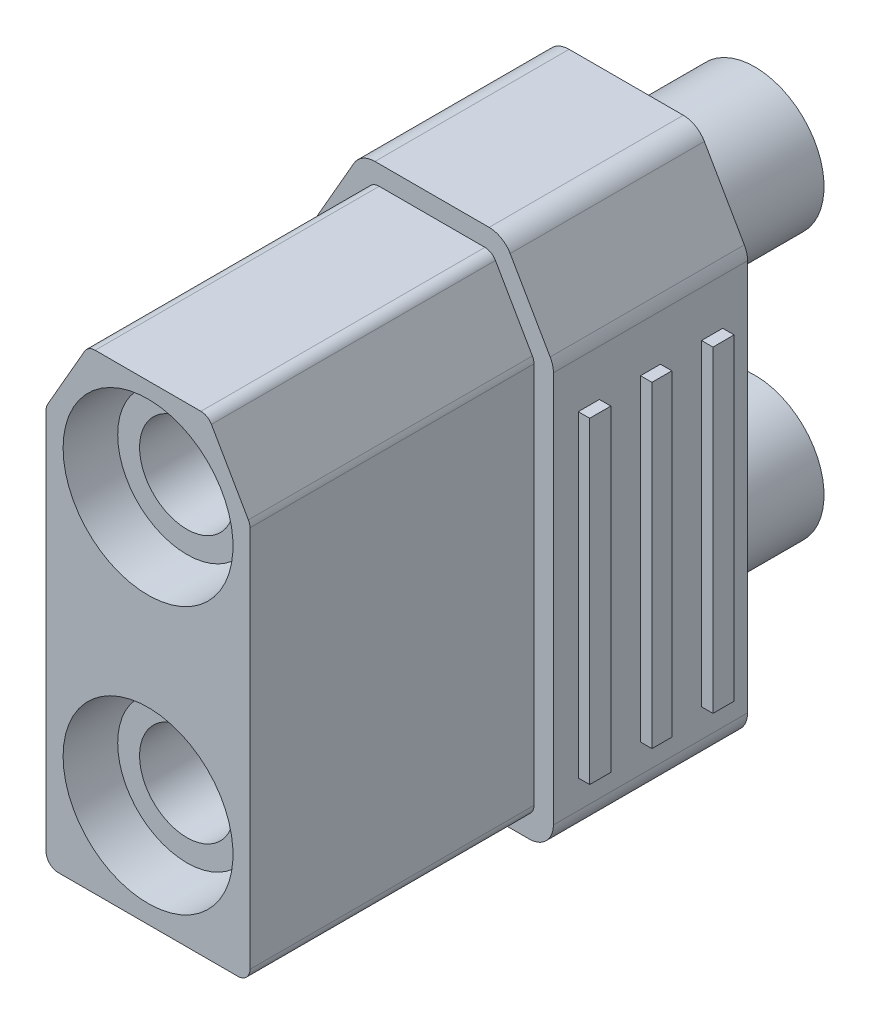
SolidWorks part; units mm, degrees
ref_plane "Front Plane" through (0, 0, 0) normal (0, 0, 1) x (1, 0, 0)
ref_plane "Top Plane" through (0, 0, 0) normal (0, 1, 0) x (1, 0, 0)
ref_plane "Right Plane" through (0, 0, 0) normal (1, 0, 0) x (0, 0, -1)
sketch "Sketch1" plane through (0, 0, 0) normal (0, 0, 1) x (1, 0, 0)
  line L0 (-5, 8.7) -> (-2.931, 12.3)
  line L1 (-5, 8.7) -> (5, 8.7) construction
  line L2 (-5, 8.7) -> (-5, -8.7)
  line L3 (-5, -8.7) -> (5, -8.7)
  line L4 (5, 8.7) -> (5, -8.7)
  line L5 (-5, 8.7) -> (5, -8.7) construction
  line L6 (-5, -8.7) -> (5, 8.7) construction
  line L7 (-2.931, 12.3) -> (2.931, 12.3)
  line L8 (2.931, 12.3) -> (5, 8.7)
  line L9 (0, 0) -> (0, 24.3333) construction
  point P0 (0, 0)
  dimension "D1" = 10
  dimension "D2" = 21
  dimension "D3" = 3.6
extrude "Boss-Extrude1" add sketch "Sketch1" along normal blind 8
sketch "Sketch2" plane through (0, 0, 8) normal (0, 0, 1) x (1, 0, 0)
  line L12 (-4.2, 8.4865) -> (-4.2, -7.9)
  line L13 (-4.2, -7.9) -> (4.2, -7.9)
  line L14 (4.2, -7.9) -> (4.2, 8.4865)
  line L15 (4.2, 8.4865) -> (2.4681, 11.5)
  line L16 (2.4681, 11.5) -> (-2.4681, 11.5)
  line L17 (-2.4681, 11.5) -> (-4.2, 8.4865)
  line L18 (-4.2, 8.4865) -> (-4.2, -7.9)
  line L19 (-4.2, -7.9) -> (4.2, -7.9)
  line L20 (4.2, -7.9) -> (4.2, 8.4865)
  line L21 (4.2, 8.4865) -> (2.4681, 11.5)
  line L22 (2.4681, 11.5) -> (-2.4681, 11.5)
  line L23 (-2.4681, 11.5) -> (-4.2, 8.4865)
  dimension "D1" = 0.8
extrude "Boss-Extrude2" add sketch "Sketch2" along normal blind 11.7
sketch "Sketch3" plane through (0, 0, 0) normal (0, 0, -1) x (-1, 0, 0)
  line L0 (0, -8.7) -> (0, 0) construction
  line L1 (5, -8.7) -> (-5, -8.7) construction
  line L2 (0, 0) -> (0, 12.8337) construction
  circle A0 centre (0, -3.65) radius 3.5
  circle A1 centre (0, 7.35) radius 3.5
  dimension "D3" = 7
  dimension "D4" = 7
  dimension "D1" = 5.05
  dimension "D2" = 11
extrude "Cut-Extrude1" cut sketch "Sketch3" against normal through all
sketch "Sketch4" plane through (0, 0, 0) normal (0, 0, -1) x (-1, 0, 0)
  circle A0 centre (0, 7.35) radius 2.85
  circle A1 centre (0, -3.65) radius 2.85
  dimension "D1" = 5.7
  dimension "D2" = 5.7
extrude "Extrude-Thin1" add sketch "Sketch4" along normal blind 5.3 and the other way offset from surface (18.1 mm away) 1.6 separate body thin other way up to face at (-3.5, 7.35, 19.7) thin type one direction reverse wall 0.9
sketch "Sketch5" plane through (5, 0, 0) normal (1, 0, 0) x (0, 0, -1)
  line L0 (-4, -8.7) -> (-4, 8.7) construction
  line L1 (-8, -8.7) -> (0, -8.7) construction
  line L2 (-8, 8.7) -> (0, 8.7) construction
  line L3 (-8, 0) -> (0, 0) construction
  line L4 (-8, -8.7) -> (-8, 8.7) construction
  line L6 (-4.41, -6.535) -> (-3.59, -6.535)
  line L7 (-4.41, -6.535) -> (-4.41, 6.535)
  line L8 (-4.41, 6.535) -> (-3.59, 6.535)
  line L9 (-3.59, -6.535) -> (-3.59, 6.535)
  line L10 (-4.41, -6.535) -> (-3.59, 6.535) construction
  line L11 (-4.41, 6.535) -> (-3.59, -6.535) construction
  line L12 (-6.975, -6.535) -> (-6.105, -6.535)
  line L13 (-6.975, -6.535) -> (-6.975, 6.535)
  line L14 (-6.975, 6.535) -> (-6.105, 6.535)
  line L15 (-6.105, -6.535) -> (-6.105, 6.535)
  line L16 (-6.975, -6.535) -> (-6.105, 6.535) construction
  line L17 (-6.975, 6.535) -> (-6.105, -6.535) construction
  line L18 (-1.895, -6.535) -> (-1.025, -6.535)
  line L19 (-1.895, -6.535) -> (-1.895, 6.535)
  line L20 (-1.895, 6.535) -> (-1.025, 6.535)
  line L21 (-1.025, -6.535) -> (-1.025, 6.535)
  line L22 (-1.895, -6.535) -> (-1.025, 6.535) construction
  line L23 (-1.895, 6.535) -> (-1.025, -6.535) construction
  point P11 (-4, 0)
  point P16 (-6.54, 0)
  point P21 (-1.46, 0)
  dimension "D1" = 0.82
  dimension "D2" = 13.07
  dimension "D3" = 0.87
  dimension "D4" = 0.87
  dimension "D5" = 5.95
extrude "Boss-Extrude3" add sketch "Sketch5" along normal blind 0.47
mirror "Mirror1" about plane through (0, 0, 0) normal (1, 0, 0) of "Boss-Extrude3"
fillet "Fillet1" radius 1 6 edges at (5, -8.7, 4) (-5, -8.7, 4) (-5, 8.7, 4) (5, 8.7, 4) (-2.931, 12.3, 4) (2.931, 12.3, 4)
fillet "Fillet2" radius 0.5 6 edges at (-4.2, -7.9, 13.85) (4.2, -7.9, 13.85) (4.2, 8.4865, 13.85) (2.4681, 11.5, 13.85) (-4.2, 8.4865, 13.85) (-2.4681, 11.5, 13.85)
equation "\"D3@Sketch5\"=0.87"
